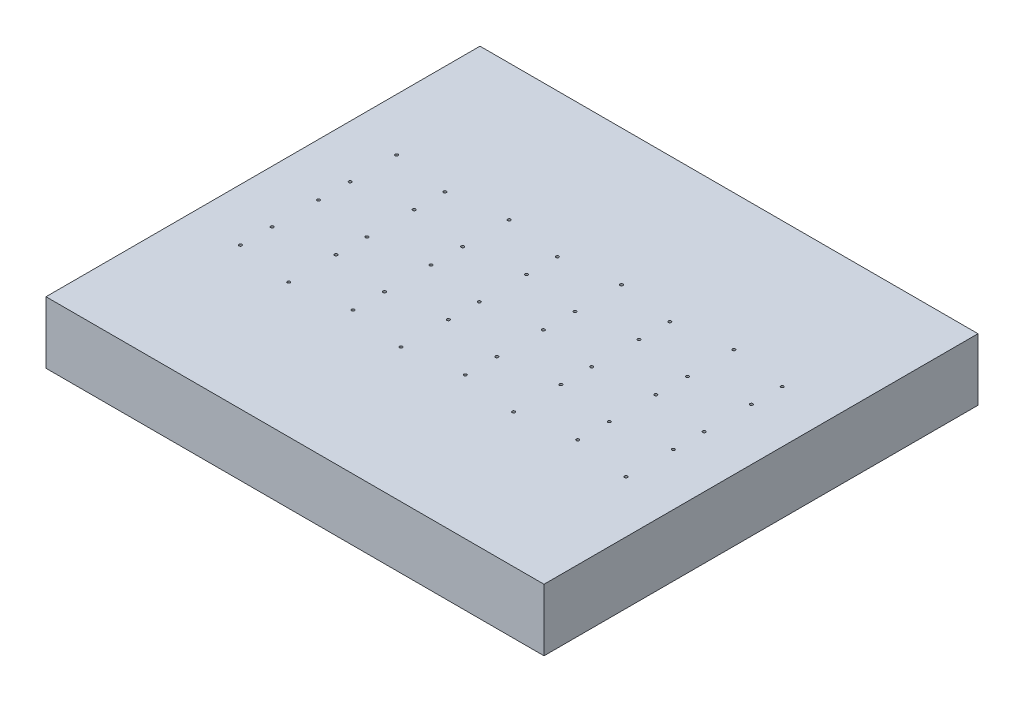
SolidWorks part; units mm, degrees
material "Polyurethane Foam Rigid"
ref_plane "X-Y Datum" through (0, 0, 0) normal (0, 0, 1) x (1, 0, 0)
ref_plane "X-Z Datum" through (0, 0, 0) normal (0, 1, 0) x (1, 0, 0)
ref_plane "Y-Z Datum" through (0, 0, 0) normal (1, 0, 0) x (0, 0, -1)
sketch "Sketch1" plane through (0, 0, 0) normal (0, 0, 1) x (1, 0, 0)
  line L1 (-153.0248, -19.05) -> (153.0248, -19.05)
  line L2 (-153.0248, -19.05) -> (-153.0248, 19.05)
  line L3 (-153.0248, 19.05) -> (153.0248, 19.05)
  line L4 (153.0248, -19.05) -> (153.0248, 19.05)
  line L5 (-153.0248, -19.05) -> (153.0248, 19.05) construction
  line L6 (-153.0248, 19.05) -> (153.0248, -19.05) construction
  point P0 (0, 0)
  dimension "D1" = 38.1
  dimension "D2" = 306.0497
extrude "Boss-Extrude1" add sketch "Sketch1" against normal blind 254
sketch "Sketch3" plane through (0, 19.05, 0) normal (0, 1, 0) x (1, 0, 0)
  line L1 (153.0248, 0) -> (-153.0248, 0) construction
  circle A0 centre (-135.6657, 51.2834) radius 3.5
  circle A1 centre (139.8613, 51.2834) radius 3.5
  dimension "D1" = 7
  dimension "D2" = 7
  dimension "D4" = 51.2834
  dimension "D5" = 51.2834
sketch "Sketch4" plane through (0, 19.05, 0) normal (0, 1, 0) x (1, 0, 0)
  line L4 (-153.0248, 0) -> (153.0248, 0)
  line L5 (153.0248, 0) -> (153.0248, 254)
  line L6 (153.0248, 254) -> (-153.0248, 254)
  line L7 (-153.0248, 254) -> (-153.0248, 0)
  line L8 (-153.0248, 0) -> (153.0248, 0)
  line L9 (153.0248, 0) -> (153.0248, 254)
  line L10 (153.0248, 254) -> (-153.0248, 254)
  line L11 (-153.0248, 254) -> (-153.0248, 0)
  circle A0 centre (17.4258, 106.6361) radius 0.875 construction
  circle A1 centre (51.9258, 111.451) radius 0.875 construction
  circle A2 centre (51.9258, 82.3911) radius 0.875 construction
  circle A3 centre (121.0138, 82.3911) radius 0.875 construction
  circle A4 centre (86.5138, 87.2061) radius 0.875 construction
  circle A5 centre (121.0138, 111.451) radius 0.875 construction
  circle A6 centre (86.5138, 106.6361) radius 0.875 construction
  circle A7 centre (121.0138, 130.3921) radius 0.875 construction
  circle A8 centre (86.5138, 135.207) radius 0.875 construction
  circle A9 centre (86.5138, 154.6421) radius 0.875 construction
  circle A10 centre (121.0138, 159.457) radius 0.875 construction
  circle A11 centre (121.0138, 178.393) radius 0.875 construction
  circle A12 centre (86.5138, 183.2079) radius 0.875 construction
  circle A13 centre (17.4258, 135.207) radius 0.875 construction
  circle A14 centre (51.9258, 159.457) radius 0.875 construction
  circle A15 centre (51.9258, 178.393) radius 0.875 construction
  circle A16 centre (17.4258, 183.2079) radius 0.875 construction
  circle A17 centre (17.4258, 154.6421) radius 0.875 construction
  circle A18 centre (51.9258, 130.3921) radius 0.875 construction
  circle A19 centre (17.4258, 87.2061) radius 0.875 construction
  circle A20 centre (-17.1622, 82.3911) radius 0.875 construction
  circle A21 centre (-51.6622, 87.2061) radius 0.875 construction
  circle A22 centre (-51.6622, 106.6361) radius 0.875 construction
  circle A23 centre (-17.1622, 111.451) radius 0.875 construction
  circle A24 centre (-17.1622, 130.3921) radius 0.875 construction
  circle A25 centre (-51.6622, 135.207) radius 0.875 construction
  circle A26 centre (-17.1622, 159.457) radius 0.875 construction
  circle A27 centre (-51.6622, 154.6421) radius 0.875 construction
  circle A28 centre (-17.1622, 178.393) radius 0.875 construction
  circle A29 centre (-51.6622, 183.2079) radius 0.875 construction
  circle A30 centre (-86.2502, 159.457) radius 0.875 construction
  circle A31 centre (-86.2502, 130.3921) radius 0.875 construction
  circle A32 centre (-86.2502, 111.451) radius 0.875 construction
  circle A33 centre (-86.2502, 82.3911) radius 0.875 construction
  circle A34 centre (-120.7502, 87.2061) radius 0.875 construction
  circle A35 centre (-120.7502, 106.6361) radius 0.875 construction
  circle A36 centre (-120.7502, 135.207) radius 0.875 construction
  circle A37 centre (-86.2502, 178.393) radius 0.875 construction
  circle A38 centre (-120.7502, 154.6421) radius 0.875 construction
  circle A39 centre (-120.7502, 183.2079) radius 0.875 construction
  circle A40 centre (17.4258, 106.6361) radius 0.875
  circle A41 centre (51.9258, 111.451) radius 0.875
  circle A42 centre (51.9258, 82.3911) radius 0.875
  circle A43 centre (121.0138, 82.3911) radius 0.875
  circle A44 centre (86.5138, 87.2061) radius 0.875
  circle A45 centre (121.0138, 111.451) radius 0.875
  circle A46 centre (86.5138, 106.6361) radius 0.875
  circle A47 centre (121.0138, 130.3921) radius 0.875
  circle A48 centre (86.5138, 135.207) radius 0.875
  circle A49 centre (86.5138, 154.6421) radius 0.875
  circle A50 centre (121.0138, 159.457) radius 0.875
  circle A51 centre (121.0138, 178.393) radius 0.875
  circle A52 centre (86.5138, 183.2079) radius 0.875
  circle A53 centre (17.4258, 135.207) radius 0.875
  circle A54 centre (51.9258, 159.457) radius 0.875
  circle A55 centre (51.9258, 178.393) radius 0.875
  circle A56 centre (17.4258, 183.2079) radius 0.875
  circle A57 centre (17.4258, 154.6421) radius 0.875
  circle A58 centre (51.9258, 130.3921) radius 0.875
  circle A59 centre (17.4258, 87.2061) radius 0.875
  circle A60 centre (-17.1622, 82.3911) radius 0.875
  circle A61 centre (-51.6622, 87.2061) radius 0.875
  circle A62 centre (-51.6622, 106.6361) radius 0.875
  circle A63 centre (-17.1622, 111.451) radius 0.875
  circle A64 centre (-17.1622, 130.3921) radius 0.875
  circle A65 centre (-51.6622, 135.207) radius 0.875
  circle A66 centre (-17.1622, 159.457) radius 0.875
  circle A67 centre (-51.6622, 154.6421) radius 0.875
  circle A68 centre (-17.1622, 178.393) radius 0.875
  circle A69 centre (-51.6622, 183.2079) radius 0.875
  circle A70 centre (-86.2502, 159.457) radius 0.875
  circle A71 centre (-86.2502, 130.3921) radius 0.875
  circle A72 centre (-86.2502, 111.451) radius 0.875
  circle A73 centre (-86.2502, 82.3911) radius 0.875
  circle A74 centre (-120.7502, 87.2061) radius 0.875
  circle A75 centre (-120.7502, 106.6361) radius 0.875
  circle A76 centre (-120.7502, 135.207) radius 0.875
  circle A77 centre (-86.2502, 178.393) radius 0.875
  circle A78 centre (-120.7502, 154.6421) radius 0.875
  circle A79 centre (-120.7502, 183.2079) radius 0.875
  dimension "D1" = 0
extrude "Cut-Extrude3" cut sketch "Sketch4" against normal through all contours A78 | A79 | A76 | A75 | A74 | A73 | A61 | A60 | A62 | A72 | A71 | A70 | A77 | A69 | A67 | A65 | A68 | A66 | A64 | A63 | A59 | A42 | A44 | A43 | A45 | A46 | A41 | A40 | A57 | A54 | A58 | A53 | A47 | A49 | A56 | A55 | A50 | A51 | A48 | A52
sketch "Sketch5" plane through (0, 0, -254) normal (0, 0, -1) x (-1, 0, 0)
  line L1 (-153.0248, 19.05) -> (153.0248, 19.05)
  line L2 (-153.0248, 19.05) -> (-153.0248, -19.05)
  line L3 (-153.0248, -19.05) -> (153.0248, -19.05)
  line L4 (153.0248, 19.05) -> (153.0248, -19.05)
  line L5 (-153.0248, 19.05) -> (153.0248, -19.05) construction
  line L6 (-153.0248, -19.05) -> (153.0248, 19.05) construction
  point P4 (0, 0)
extrude "Boss-Extrude2" add sketch "Sketch5" along normal blind 12.7
